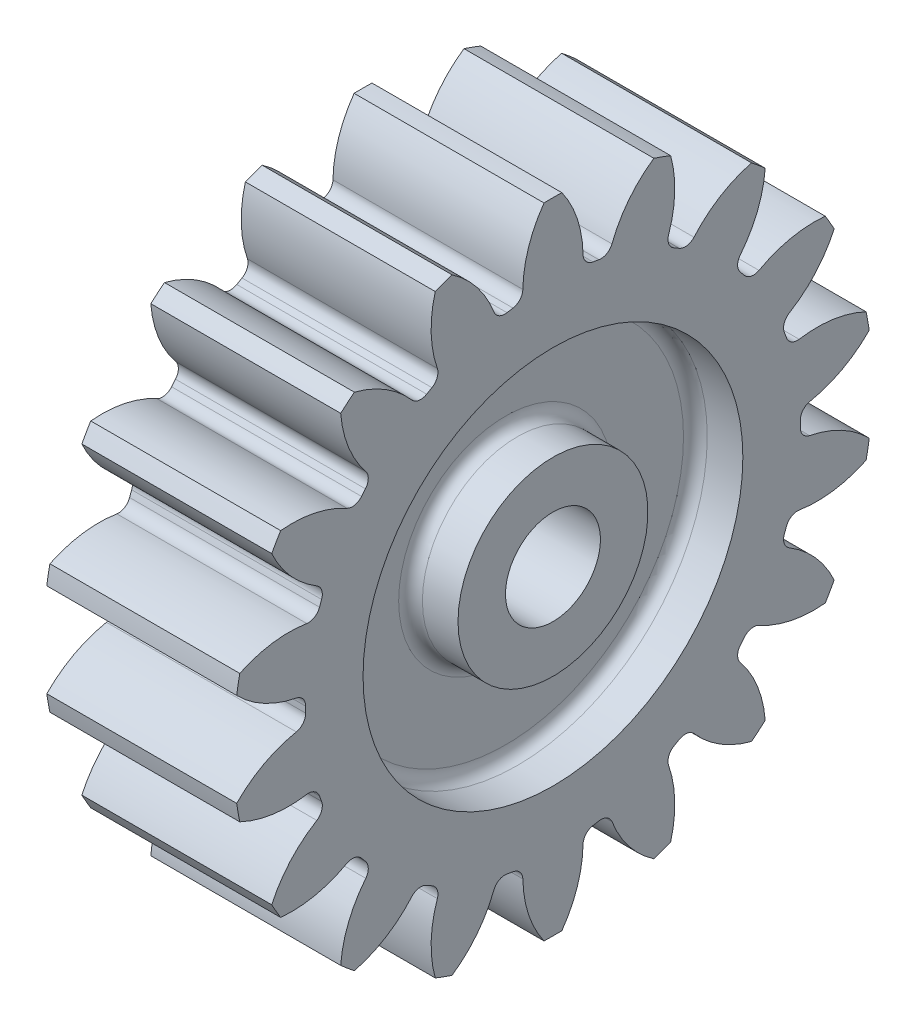
SolidWorks part; units mm, degrees
ref_plane "Front Plane" through (0, 0, 0) normal (0, 0, 1) x (1, 0, 0)
ref_plane "Top Plane" through (0, 0, 0) normal (0, 1, 0) x (1, 0, 0)
ref_plane "Right Plane" through (0, 0, 0) normal (1, 0, 0) x (0, 0, -1)
sketch "Sketch1" plane through (0, 0, 0) normal (0, 0, 1) x (1, 0, 0)
  line L0 (-34.9826, 0) -> (32.9692, 0) construction
  line L1 (0, 42.7609) -> (0, 6.35) construction
  line L2 (12.7, 42.7609) -> (-12.7, 42.7609)
  line L3 (-12.7, 42.7609) -> (-12.7, 25.4)
  line L4 (-12.7, 25.4) -> (-7.9375, 25.4)
  line L5 (-6.35, 23.8125) -> (-6.35, 14.2875)
  line L6 (-7.9375, 12.7) -> (-12.7, 12.7)
  line L7 (-12.7, 12.7) -> (-12.7, 6.35)
  line L8 (-12.7, 6.35) -> (12.7, 6.35)
  line L9 (-7.9375, 25.4) -> (-7.9375, 12.7) construction
  line L10 (-6.35, 19.05) -> (-3.3212, 19.05) construction
  line L14 (7.9375, 25.4) -> (7.9375, 12.7) construction
  line L15 (12.7, 12.7) -> (12.7, 6.35)
  line L16 (7.9375, 12.7) -> (12.7, 12.7)
  line L17 (6.35, 23.8125) -> (6.35, 14.2875)
  line L18 (12.7, 25.4) -> (7.9375, 25.4)
  line L19 (12.7, 42.7609) -> (12.7, 25.4)
  arc A0 (-6.35, 23.8125) -> (-7.9375, 25.4) centre (-7.9375, 23.8125) ccw
  arc A3 (6.35, 23.8125) -> (7.9375, 25.4) centre (7.9375, 23.8125) cw
  arc A4 (-6.35, 14.2875) -> (-7.9375, 12.7) centre (-7.9375, 14.2875) cw
  arc A5 (6.35, 14.2875) -> (7.9375, 12.7) centre (7.9375, 14.2875) ccw
  point P4 (0, 0)
  dimension "D1" = 3.175
  dimension "D5" = 6.35
  dimension "D2" = 25.4
  dimension "D3" = 25.4
  dimension "D4" = 50.8
  dimension "D6" = 6.35
  dimension "D7" = 85.5218
revolve "Revolve1" add sketch "Sketch1" angle 360 about L0
sketch "Sketch2" plane through (12.7, 0, 0) normal (1, 0, 0) x (0, 0, -1)
  line L0 (0, 42.7609) -> (0, -42.7609) construction
  line L1 (-42.7609, 0) -> (42.7609, 0) construction
  line L2 (0, 42.7609) -> (1.1937, 42.7442)
  line L3 (0, 42.7609) -> (-1.1937, 42.7442)
  line L4 (14.6251, 40.1821) -> (15.7411, 39.7582)
  line L5 (14.6251, 40.1821) -> (13.4977, 40.5747)
  line L6 (27.4862, 32.7567) -> (28.3899, 31.9767)
  line L7 (27.4862, 32.7567) -> (26.5611, 33.5113)
  line L8 (37.032, 21.3805) -> (37.6144, 20.3384)
  line L9 (37.032, 21.3805) -> (36.4208, 22.4059)
  line L10 (42.1113, 7.4254) -> (42.3021, 6.2469)
  line L11 (42.1113, 7.4254) -> (41.8876, 8.598)
  line L12 (42.1113, -7.4254) -> (41.8876, -8.598)
  line L13 (42.1113, -7.4254) -> (42.3021, -6.2469)
  line L14 (37.032, -21.3804) -> (36.4208, -22.4059)
  line L15 (37.032, -21.3804) -> (37.6144, -20.3384)
  line L16 (27.4862, -32.7567) -> (26.5611, -33.5113)
  line L17 (27.4862, -32.7567) -> (28.3899, -31.9767)
  line L18 (14.6251, -40.1821) -> (13.4977, -40.5747)
  line L19 (14.6251, -40.1821) -> (15.7411, -39.7582)
  line L20 (0, -42.7609) -> (-1.1937, -42.7442)
  line L21 (0, -42.7609) -> (1.1937, -42.7442)
  line L22 (-14.6251, -40.1821) -> (-15.7411, -39.7582)
  line L23 (-14.6251, -40.1821) -> (-13.4977, -40.5747)
  line L24 (-27.4862, -32.7567) -> (-28.3899, -31.9767)
  line L25 (-27.4862, -32.7567) -> (-26.5611, -33.5113)
  line L26 (-37.032, -21.3805) -> (-37.6144, -20.3384)
  line L27 (-37.032, -21.3805) -> (-36.4208, -22.4059)
  line L28 (-42.1113, -7.4254) -> (-42.3021, -6.2469)
  line L29 (-42.1113, -7.4254) -> (-41.8876, -8.598)
  line L30 (-42.1113, 7.4254) -> (-41.8876, 8.598)
  line L31 (-42.1113, 7.4254) -> (-42.3021, 6.2469)
  line L32 (-37.032, 21.3805) -> (-36.4208, 22.4059)
  line L33 (-37.032, 21.3805) -> (-37.6144, 20.3384)
  line L34 (-27.4862, 32.7567) -> (-26.5611, 33.5113)
  line L35 (-27.4862, 32.7567) -> (-28.3899, 31.9767)
  line L36 (-14.6251, 40.1821) -> (-13.4977, 40.5747)
  line L37 (-14.6251, 40.1821) -> (-15.7411, 39.7582)
  circle A0 centre (0, 0) radius 38.5191 construction
  circle A2 centre (0, 0) radius 33.0835
  circle A3 centre (0, 0) radius 42.7609 construction
  arc A4 (4.0259, 34.2028) -> (5.3462, 32.6487) centre (5.6007, 34.2028) ccw
  arc A5 (4.027, 34.1443) -> (1.1937, 42.7442) centre (-11.2109, 33.8908) ccw
  arc A6 (-4.0259, 34.2028) -> (-5.3462, 32.6487) centre (-5.6007, 34.2028) cw
  arc A7 (-4.027, 34.1443) -> (-1.1937, 42.7442) centre (11.2109, 33.8908) cw
  arc A8 (7.8939, 33.4625) -> (13.4977, 40.5747) centre (22.1261, 28.0126) cw
  arc A9 (7.9149, 33.517) -> (6.1427, 32.5082) centre (6.4351, 34.0556) cw
  arc A10 (15.4622, 30.7079) -> (15.7411, 39.7582) centre (1.0565, 35.6813) ccw
  arc A11 (15.4811, 30.7632) -> (16.1903, 28.8512) centre (16.961, 30.2245) ccw
  arc A12 (18.8627, 28.7446) -> (26.5611, 33.5113) centre (30.3726, 18.7556) cw
  arc A13 (18.9011, 28.7886) -> (16.8907, 28.4468) centre (17.6947, 29.8009) cw
  arc A14 (25.0324, 23.5676) -> (28.3899, 31.9767) centre (13.1965, 33.1681) ccw
  arc A15 (25.0691, 23.613) -> (25.0816, 21.5739) centre (26.2755, 22.6008) ccw
  arc A16 (27.5564, 20.5596) -> (36.4208, 22.4059) centre (34.9557, 7.2365) cw
  arc A17 (27.6075, 20.5879) -> (25.6015, 20.9543) centre (26.8201, 21.9517) cw
  arc A18 (31.5834, 13.5847) -> (37.6144, 20.3384) centre (23.7448, 26.6543) ccw
  arc A19 (31.6334, 13.6149) -> (30.9477, 11.6944) centre (32.4208, 12.251) ccw
  arc A20 (32.9263, 9.8949) -> (41.8876, 8.598) centre (35.3227, -5.1555) cw
  arc A21 (32.9841, 9.904) -> (31.2243, 10.9344) centre (32.7106, 11.4549) cw
  arc A22 (34.3249, 1.9633) -> (42.3021, 6.2469) centre (31.4291, 16.9257) ccw
  arc A23 (34.3822, 1.9745) -> (33.081, 0.4044) centre (34.6557, 0.4236) ccw
  arc A24 (34.3249, -1.9633) -> (42.3021, -6.2469) centre (31.4291, -16.9257) cw
  arc A25 (34.3822, -1.9745) -> (33.081, -0.4044) centre (34.6557, -0.4236) cw
  arc A26 (32.9263, -9.8949) -> (41.8876, -8.598) centre (35.3227, 5.1555) ccw
  arc A27 (32.9841, -9.904) -> (31.2243, -10.9344) centre (32.7106, -11.4549) ccw
  arc A28 (31.5834, -13.5847) -> (37.6144, -20.3384) centre (23.7448, -26.6543) cw
  arc A29 (31.6334, -13.6149) -> (30.9477, -11.6944) centre (32.4208, -12.251) cw
  arc A30 (27.5564, -20.5596) -> (36.4208, -22.4059) centre (34.9557, -7.2365) ccw
  arc A31 (27.6075, -20.5879) -> (25.6015, -20.9543) centre (26.8201, -21.9517) ccw
  arc A32 (25.0324, -23.5676) -> (28.3899, -31.9767) centre (13.1965, -33.1681) cw
  arc A33 (25.0691, -23.613) -> (25.0816, -21.5739) centre (26.2755, -22.6008) cw
  arc A34 (18.8627, -28.7446) -> (26.5611, -33.5113) centre (30.3726, -18.7556) ccw
  arc A35 (18.9011, -28.7886) -> (16.8907, -28.4468) centre (17.6947, -29.8009) ccw
  arc A36 (15.4622, -30.7079) -> (15.7411, -39.7582) centre (1.0565, -35.6813) cw
  arc A37 (15.4811, -30.7632) -> (16.1903, -28.8512) centre (16.961, -30.2245) cw
  arc A38 (7.8939, -33.4625) -> (13.4977, -40.5747) centre (22.1261, -28.0126) ccw
  arc A39 (7.9149, -33.517) -> (6.1427, -32.5082) centre (6.4351, -34.0556) ccw
  arc A40 (4.027, -34.1443) -> (1.1937, -42.7442) centre (-11.2109, -33.8908) cw
  arc A41 (4.0259, -34.2028) -> (5.3462, -32.6487) centre (5.6007, -34.2028) cw
  arc A42 (-4.027, -34.1443) -> (-1.1937, -42.7442) centre (11.2109, -33.8908) ccw
  arc A43 (-4.0259, -34.2028) -> (-5.3462, -32.6487) centre (-5.6007, -34.2028) ccw
  arc A44 (-7.8939, -33.4625) -> (-13.4977, -40.5747) centre (-22.1261, -28.0126) cw
  arc A45 (-7.9149, -33.517) -> (-6.1427, -32.5082) centre (-6.4351, -34.0556) cw
  arc A46 (-15.4622, -30.7079) -> (-15.7411, -39.7582) centre (-1.0565, -35.6813) ccw
  arc A47 (-15.4811, -30.7632) -> (-16.1903, -28.8512) centre (-16.961, -30.2245) ccw
  arc A48 (-18.8627, -28.7446) -> (-26.5611, -33.5113) centre (-30.3726, -18.7556) cw
  arc A49 (-18.9011, -28.7886) -> (-16.8907, -28.4468) centre (-17.6947, -29.8009) cw
  arc A50 (-25.0324, -23.5676) -> (-28.3899, -31.9767) centre (-13.1965, -33.1681) ccw
  arc A51 (-25.0691, -23.613) -> (-25.0816, -21.5739) centre (-26.2755, -22.6008) ccw
  arc A52 (-27.5564, -20.5596) -> (-36.4208, -22.4059) centre (-34.9557, -7.2365) cw
  arc A53 (-27.6075, -20.5879) -> (-25.6015, -20.9543) centre (-26.8201, -21.9517) cw
  arc A54 (-31.5834, -13.5847) -> (-37.6144, -20.3384) centre (-23.7448, -26.6543) ccw
  arc A55 (-31.6334, -13.6149) -> (-30.9477, -11.6944) centre (-32.4208, -12.251) ccw
  arc A56 (-32.9263, -9.8949) -> (-41.8876, -8.598) centre (-35.3227, 5.1555) cw
  arc A57 (-32.9841, -9.904) -> (-31.2243, -10.9344) centre (-32.7106, -11.4549) cw
  arc A58 (-34.3249, -1.9633) -> (-42.3021, -6.2469) centre (-31.4291, -16.9257) ccw
  arc A59 (-34.3822, -1.9745) -> (-33.081, -0.4044) centre (-34.6557, -0.4236) ccw
  arc A60 (-34.3249, 1.9633) -> (-42.3021, 6.2469) centre (-31.4291, 16.9257) cw
  arc A61 (-34.3822, 1.9745) -> (-33.081, 0.4044) centre (-34.6557, 0.4236) cw
  arc A62 (-32.9263, 9.8949) -> (-41.8876, 8.598) centre (-35.3227, -5.1555) ccw
  arc A63 (-32.9841, 9.904) -> (-31.2243, 10.9344) centre (-32.7106, 11.4549) ccw
  arc A64 (-31.5834, 13.5847) -> (-37.6144, 20.3384) centre (-23.7448, 26.6543) cw
  arc A65 (-31.6334, 13.6149) -> (-30.9477, 11.6944) centre (-32.4208, 12.251) cw
  arc A66 (-27.5564, 20.5596) -> (-36.4208, 22.4059) centre (-34.9557, 7.2365) ccw
  arc A67 (-27.6075, 20.5879) -> (-25.6015, 20.9543) centre (-26.8201, 21.9517) ccw
  arc A68 (-25.0324, 23.5676) -> (-28.3899, 31.9767) centre (-13.1965, 33.1681) cw
  arc A69 (-25.0691, 23.613) -> (-25.0816, 21.5739) centre (-26.2755, 22.6008) cw
  arc A70 (-18.8627, 28.7446) -> (-26.5611, 33.5113) centre (-30.3726, 18.7556) ccw
  arc A71 (-18.9011, 28.7886) -> (-16.8907, 28.4468) centre (-17.6947, 29.8009) ccw
  arc A72 (-15.4622, 30.7079) -> (-15.7411, 39.7582) centre (-1.0565, 35.6813) cw
  arc A73 (-15.4811, 30.7632) -> (-16.1903, 28.8512) centre (-16.961, 30.2245) cw
  arc A74 (-7.8939, 33.4625) -> (-13.4977, 40.5747) centre (-22.1261, 28.0126) ccw
  arc A75 (-7.9149, 33.517) -> (-6.1427, 32.5082) centre (-6.4351, 34.0556) ccw
  point P248 (0, 0)
  circle M9 centre (0, 0) radius 42.7609
  dimension "D1" = 9.6774
  dimension "D2" = 5.4356
  dimension "D4" = 15.24
  dimension "D5" = 1.5748
  dimension "D6" = 4.0259
  dimension "D7" = 18
  dimension "D3" = 1.1938
extrude "Cut-Extrude2" cut sketch "Sketch2" against normal through all both contours A45 A44 A42 A43 A2 M9 | A49 A48 A46 A47 A2 M9 | A53 A52 A50 A51 A2 M9 | A57 A56 A54 A55 A2 M9 | A61 A60 A58 A59 A2 M9 | A65 A64 A62 A63 A2 M9 | A69 A68 A66 A67 A2 M9 | A73 A72 A70 A71 A2 M9 | A74 A75 A2 A6 A7 M9 | A9 A8 A5 A4 A2 M9 | A13 A12 A10 A11 A2 M9 | A17 A16 A14 A15 A2 M9 | A21 A20 A18 A19 A2 M9 | A25 A24 A22 A23 A2 M9 | A29 A28 A26 A27 A2 M9 | A33 A32 A30 A31 A2 M9 | A37 A36 A34 A35 A2 M9 | A41 A40 A38 A39 A2 M9
